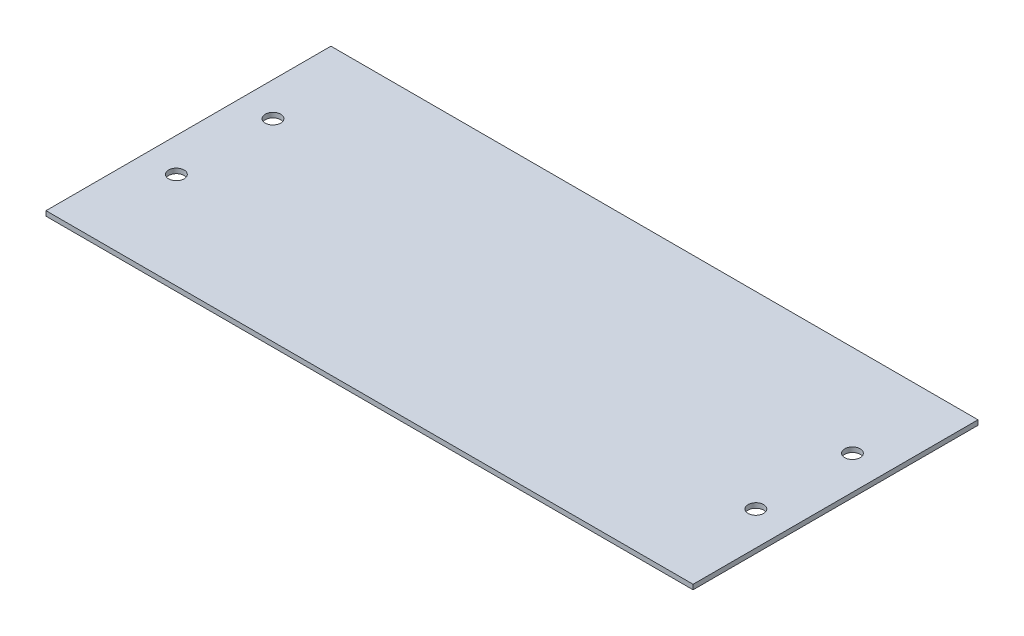
SolidWorks part; units mm, degrees
material "环氧树脂FR-4"
ref_plane "前视基准面" through (0, 0, 0) normal (0, 0, 1) x (1, 0, 0)
ref_plane "上视基准面" through (0, 0, 0) normal (0, 1, 0) x (1, 0, 0)
ref_plane "右视基准面" through (0, 0, 0) normal (1, 0, 0) x (0, 0, -1)
sketch "草图1" plane through (0, 0, 0) normal (0, 1, 0) x (1, 0, 0)
  line L1 (67, -29.5) -> (-67, -29.5)
  line L2 (67, -29.5) -> (67, 29.5)
  line L3 (67, 29.5) -> (-67, 29.5)
  line L4 (-67, -29.5) -> (-67, 29.5)
  line L5 (67, -29.5) -> (-67, 29.5) construction
  line L6 (67, 29.5) -> (-67, -29.5) construction
  point P0 (0, 0)
  dimension "D1" = 134
  dimension "D2" = 59
extrude "凸台-拉伸1" add sketch "草图1" along normal blind 1
sketch "草图2" plane through (0, 1, 0) normal (0, 1, 0) x (1, 0, 0)
  line L0 (-60, 10.5) -> (-60, -9.5) construction
  line L1 (-67, 29.5) -> (-67, -29.5) construction
  line L2 (-67, -29.5) -> (67, -29.5) construction
  line L3 (0, 0) -> (0, -29.5) construction
  line L4 (-67, -29.5) -> (67, -29.5) construction
  circle A0 centre (-60, -9.5) radius 1.6
  circle A1 centre (-60, 10.5) radius 1.6
  circle A2 centre (60, 10.5) radius 1.6
  circle A3 centre (60, -9.5) radius 1.6
  dimension "D3" = 20
  dimension "D4" = 3.2
  dimension "D1" = 7
  dimension "D2" = 20
extrude "切除-拉伸1" cut sketch "草图2" against normal through all
